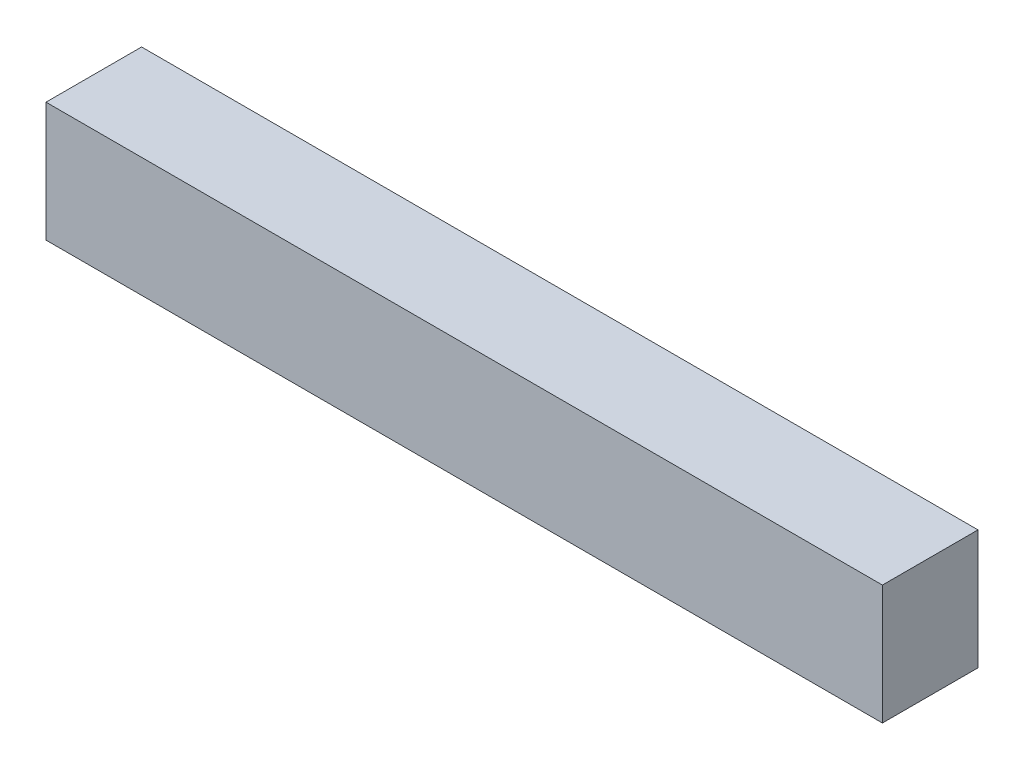
SolidWorks part; units mm, degrees
ref_plane "Front Plane" through (0, 0, 0) normal (0, 0, 1) x (1, 0, 0)
ref_plane "Top Plane" through (0, 0, 0) normal (0, 1, 0) x (1, 0, 0)
ref_plane "Right Plane" through (0, 0, 0) normal (1, 0, 0) x (0, 0, -1)
sketch "Sketch1" plane through (0, 0, 0) normal (0, 1, 0) x (1, 0, 0)
  line L1 (-17.5, -2) -> (17.5, -2)
  line L2 (-17.5, -2) -> (-17.5, 2)
  line L3 (-17.5, 2) -> (17.5, 2)
  line L4 (17.5, -2) -> (17.5, 2)
  line L5 (-17.5, -2) -> (17.5, 2) construction
  line L6 (-17.5, 2) -> (17.5, -2) construction
  point P0 (0, 0)
  dimension "D1" = 4
  dimension "D2" = 35
extrude "Boss-Extrude1" add sketch "Sketch1" along normal blind 5
